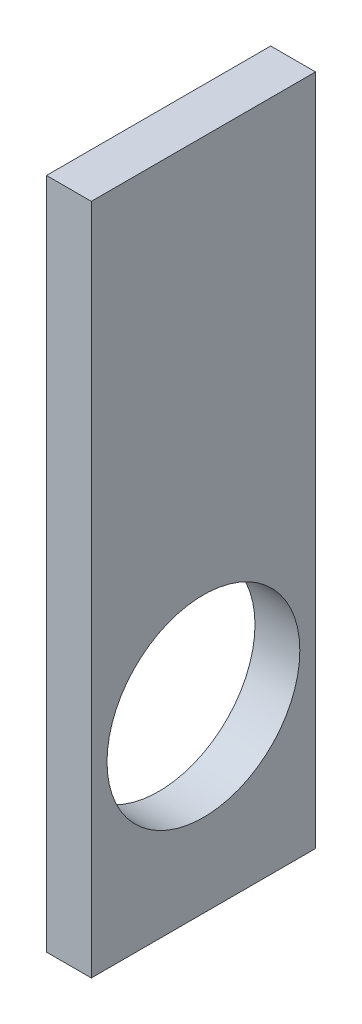
SolidWorks part; units mm, degrees
ref_plane "Front Plane" through (0, 0, 0) normal (0, 0, 1) x (1, 0, 0)
ref_plane "Top Plane" through (0, 0, 0) normal (0, 1, 0) x (1, 0, 0)
ref_plane "Right Plane" through (0, 0, 0) normal (1, 0, 0) x (0, 0, -1)
sketch "Sketch1" plane through (0, 0, 0) normal (0, 1, 0) x (1, 0, 0)
  line L1 (-5, 25) -> (5, 25)
  line L2 (-5, 25) -> (-5, -25)
  line L3 (-5, -25) -> (5, -25)
  line L4 (5, 25) -> (5, -25)
  line L5 (-5, 25) -> (5, -25) construction
  line L6 (-5, -25) -> (5, 25) construction
  point P0 (0, 0)
  dimension "D1" = 10
  dimension "D2" = 50
extrude "Boss-Extrude1" add sketch "Sketch1" along normal blind 150
sketch "Sketch2" plane through (5, 0, 0) normal (1, 0, 0) x (0, 0, -1)
  line L0 (0, 0) -> (0, 40) construction
  circle A0 centre (0, 40) radius 21.5
  dimension "D2" = 43
  dimension "D1" = 40
extrude "Cut-Extrude1" cut sketch "Sketch2" against normal blind 150
sketch "Sketch3" plane through (5, 0, 0) normal (1, 0, 0) x (0, 0, -1)
  line L0 (-21.5, 40) -> (-25, 40) construction
  line L1 (-25, 150) -> (-25, 0) construction
  circle A0 centre (0, 40) radius 21.5 construction
